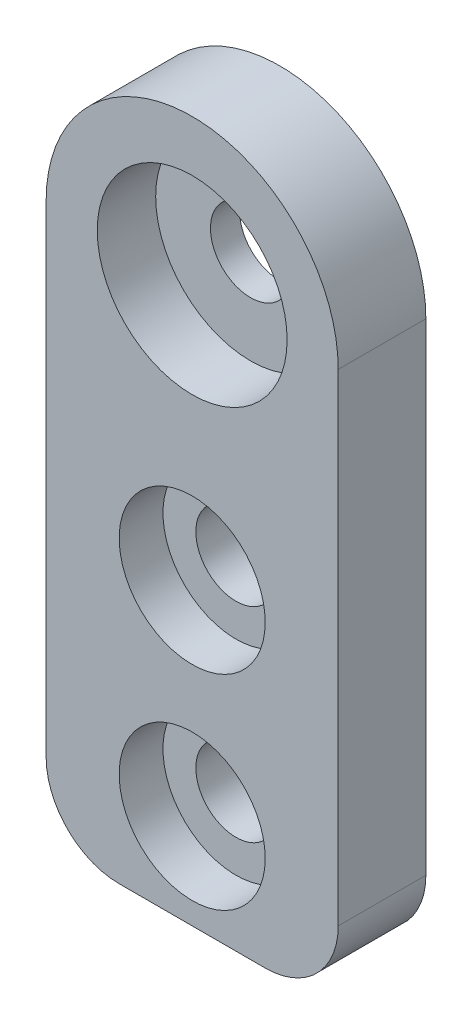
SolidWorks part; units mm, degrees
ref_plane "Спереди" through (0, 0, 0) normal (0, 0, 1) x (1, 0, 0)
ref_plane "Сверху" through (0, 0, 0) normal (0, 1, 0) x (1, 0, 0)
ref_plane "Справа" through (0, 0, 0) normal (1, 0, 0) x (0, 0, -1)
sketch "Эскиз2" plane through (0, 0, 0) normal (0, 0, 1) x (1, 0, 0)
  line L0 (0, -19) -> (0, 8) construction
  line L2 (10, 19) -> (10, -19)
  line L3 (10, -19) -> (-10, -19)
  line L4 (-10, 19) -> (-10, -19)
  line L5 (10, 19) -> (-10, -19) construction
  line L6 (10, -19) -> (-10, 19) construction
  line L7 (0, -5.5) -> (-10, -5.5) construction
  circle A0 centre (0, 1.5) radius 2.75
  circle A1 centre (0, -12.5) radius 2.75
  arc A2 (-10, 19) -> (10, 19) centre (0, 19) cw
  circle A3 centre (0, 19) radius 2.75
  point P0 (0, 0)
  dimension "D5" = 5.5
  dimension "D6" = 5.5
  dimension "D1" = 38
  dimension "D2" = 20
  dimension "D3" = 27
  dimension "D4" = 14
extrude "Бобышка-Вытянуть1" add sketch "Эскиз2" along normal blind 6
sketch "Эскиз3" plane through (0, 0, 6) normal (0, 0, 1) x (1, 0, 0)
  circle A0 centre (0, 1.5) radius 5
  circle A1 centre (0, -12.5) radius 5
  dimension "D1" = 10
  dimension "D2" = 10
extrude "Вырез-Вытянуть1" cut sketch "Эскиз3" against normal blind 3
fillet "Скругление1" radius 5 2 edges at (-10, -19, 3) (10, -19, 3)
sketch "Эскиз4" plane through (0, 0, 6) normal (0, 0, 1) x (1, 0, 0)
  circle A0 centre (0, 19) radius 6.5
  dimension "D1" = 13
extrude "Вырез-Вытянуть2" cut sketch "Эскиз4" against normal blind 4
equation "\"print_offset\"= 0.5"
equation "\"screw_m5_d\"= 5"
equation "\"screw_m5_hh_d\"= 9.5"
equation "\"nut_m5_d\"= 7.9"
equation "\"nut_m5_h\"= 3.9"
equation "\"tube_d\"= 16"
equation "\"tube_tape_d\"= 3"
equation "\"tube_tape_h\"= 11"
equation "\"D5@Эскиз2\"=\"screw_m5_d\"+\"print_offset\""
equation "\"D6@Эскиз2\"=\"D5@Эскиз2\""
equation "\"D1@Эскиз3\"=\"screw_m5_hh_d\"+\"print_offset\""
equation "\"D2@Эскиз3\"=\"D1@Эскиз3\""
equation "\"D1@Эскиз2\"=\"D3@Эскиз2\"+11"
